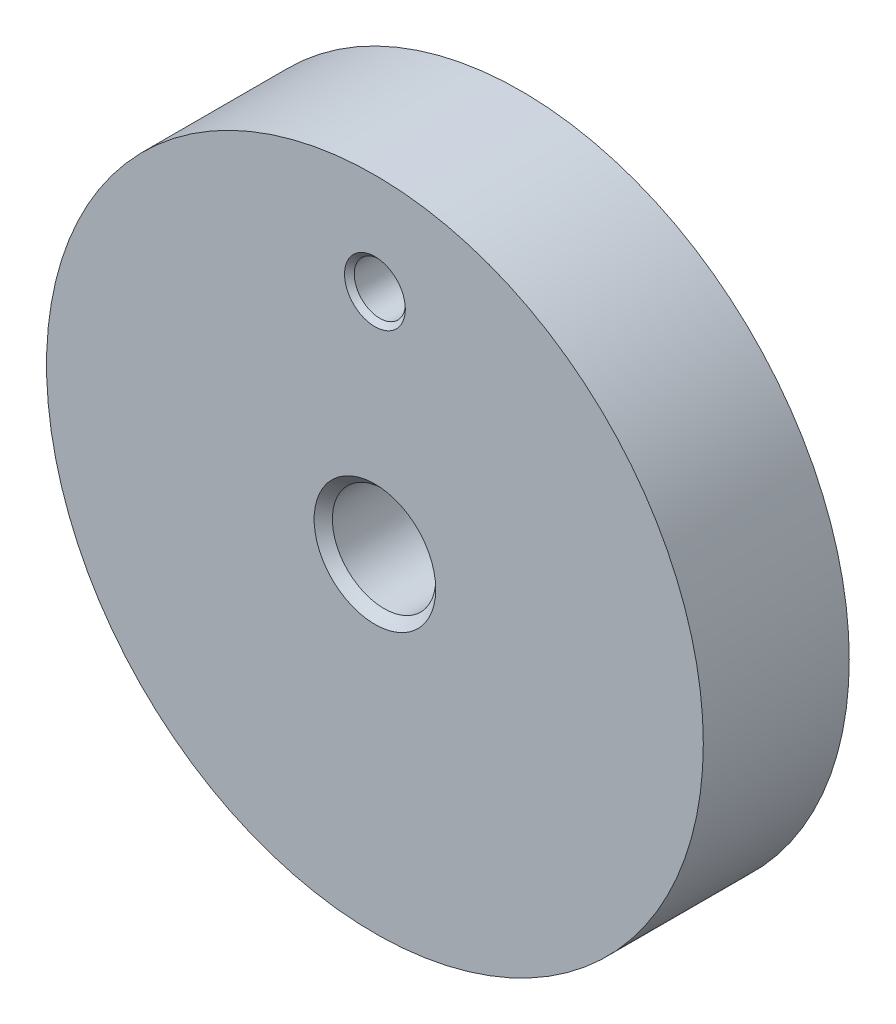
SolidWorks part; units mm, degrees
ref_plane "Piano frontale" through (0, 0, 0) normal (0, 0, 1) x (1, 0, 0)
ref_plane "Piano superiore" through (0, 0, 0) normal (0, 1, 0) x (1, 0, 0)
ref_plane "Piano destro" through (0, 0, 0) normal (1, 0, 0) x (0, 0, -1)
sketch "Sketch1" plane through (0, 0, 0) normal (0, 0, 1) x (1, 0, 0)
  circle A0 centre (0, 0) radius 27
  dimension "D1" = 54
extrude "Boss-Extrude1" add sketch "Sketch1" along normal blind 12
sketch "Sketch2" plane through (0, 0, 12) normal (0, 0, 1) x (1, 0, 0)
  circle A0 centre (0, 0) radius 5
  circle A1 centre (0, 18.697) radius 2.5
  point P3 (0, 18.697)
  dimension "D1" = 10
  dimension "D2" = 5
sketch "Sketch4" plane through (0, 0, 12) normal (0, 0, 1) x (1, 0, 0)
  circle A1 centre (0, 18.697) radius 2.5
  circle A2 centre (0, 18.697) radius 2.5
  circle A3 centre (0, 0) radius 5
  circle A4 centre (0, 0) radius 5
  point P5 (0, 0)
  dimension "D1" = 0
  dimension "D2" = 0
hole_wizard "M10 Tapped Hole2" positions "Sketch4" profile "Sketch8" tap size "M10" standard "ISO" end condition through all
cosmetic thread "Hole Thread3"
sketch "Sketch8" plane through (0, 0, 12) normal (1, 0, 0) x (0, -1, 0)
  line L0 (0, 0) -> (0, 12)
  line L1 (0, 12) -> (5, 12)
  line L2 (4.25, 11.25) -> (4.25, 0.75)
  line L3 (4.25, 0.75) -> (5, 0)
  line L5 (5, 0) -> (0, 0)
  line L6 (-4.25, 0.75) -> (-5, 0) construction
  line L7 (5, 12) -> (4.25, 11.25)
  line L8 (-5, 12) -> (-4.25, 11.25) construction
  line L11 (0, -6.35) -> (0, 107.95) construction
  dimension "Thru Tap Drill Dia." = 8.5
  dimension "Thru Tap Drill Depth" = 12
  dimension "Near C'Sink Dia." = 10
  dimension "Near C'Sink Angle" = 90
  dimension "Far C'Sink Dia." = 10
  dimension "Far C'Sink Angle" = 90
hole_wizard "M5 Tapped Hole1" positions "Sketch2" profile "Sketch9" tap size "M5" standard "ISO" end condition through all
sketch "Sketch9" plane through (0, 18.697, 12) normal (1, 0, 0) x (0, -1, 0)
  line L0 (0, 0) -> (0, 12)
  line L1 (0, 12) -> (2.5, 12)
  line L2 (2.1, 11.6) -> (2.1, 0.4)
  line L3 (2.1, 0.4) -> (2.5, 0)
  line L5 (2.5, 0) -> (0, 0)
  line L6 (-2.1, 0.4) -> (-2.5, 0) construction
  line L7 (2.5, 12) -> (2.1, 11.6)
  line L8 (-2.5, 12) -> (-2.1, 11.6) construction
  line L11 (0, -6.35) -> (0, 107.95) construction
  dimension "Thru Tap Drill Dia." = 4.2
  dimension "Thru Tap Drill Depth" = 12
  dimension "Near C'Sink Dia." = 5
  dimension "Near C'Sink Angle" = 90
  dimension "Far C'Sink Dia." = 5
  dimension "Far C'Sink Angle" = 90
cosmetic thread "Hole Thread4" parameters "D2"=5
